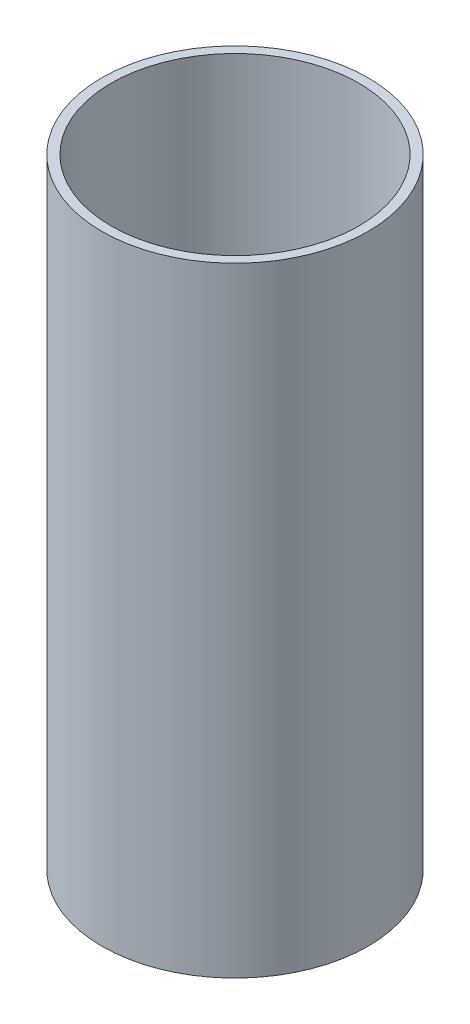
SolidWorks part; units mm, degrees
ref_plane "Front Plane" through (0, 0, 0) normal (0, 0, 1) x (1, 0, 0)
ref_plane "Top Plane" through (0, 0, 0) normal (0, 1, 0) x (1, 0, 0)
ref_plane "Right Plane" through (0, 0, 0) normal (1, 0, 0) x (0, 0, -1)
sketch "Sketch1" plane through (0, 0, 0) normal (0, 1, 0) x (1, 0, 0)
  circle A0 centre (0, 0) radius 17.2
  circle A1 centre (0, 0) radius 16
  dimension "D1" = 34.4
  dimension "D2" = 32
extrude "Boss-Extrude1" add sketch "Sketch1" along normal blind 80
